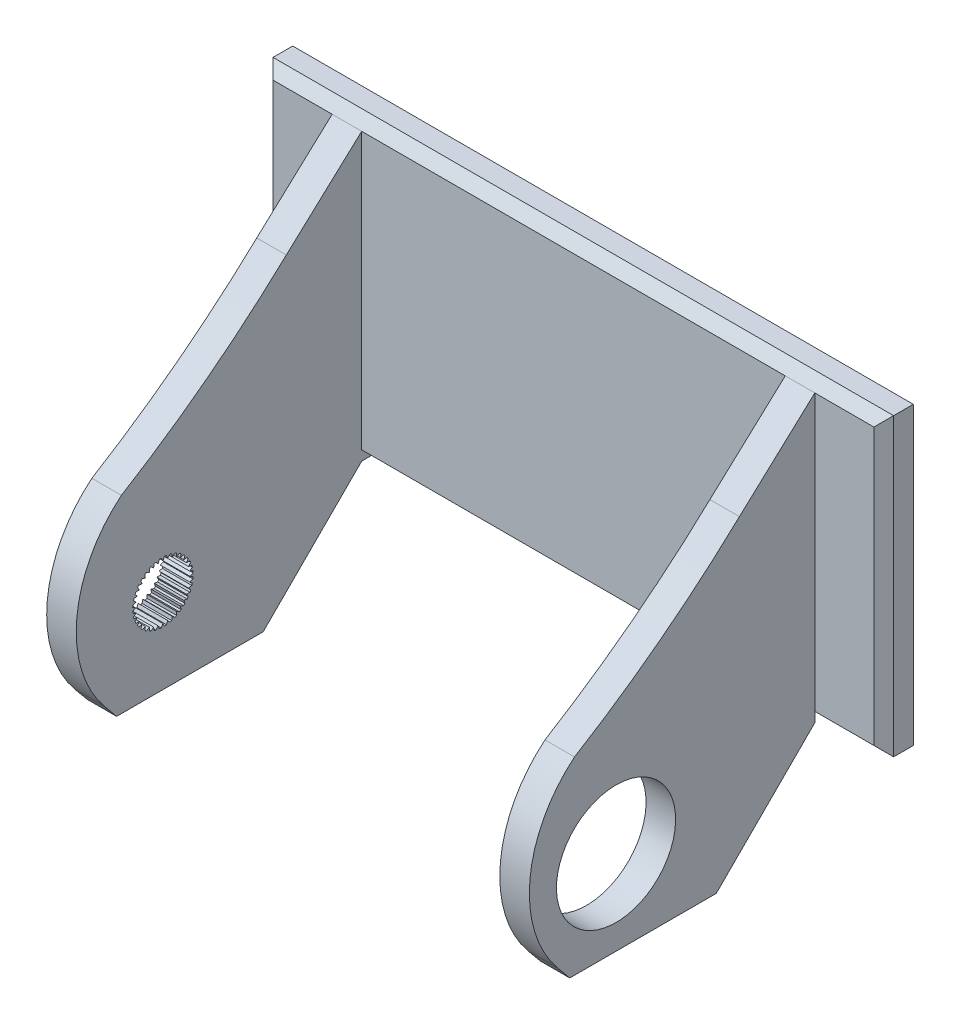
SolidWorks part; units mm, degrees
ref_plane "Front Plane" through (0, 0, 0) normal (0, 0, 1) x (1, 0, 0)
ref_plane "Top Plane" through (0, 0, 0) normal (0, 1, 0) x (1, 0, 0)
ref_plane "Right Plane" through (0, 0, 0) normal (1, 0, 0) x (0, 0, -1)
sketch "Sketch2" plane through (0, 0, 0) normal (0, 0, 1) x (1, 0, 0)
  line L1 (-31.5, -15) -> (31.5, -15)
  line L2 (-31.5, -15) -> (-31.5, 15)
  line L3 (-31.5, 15) -> (31.5, 15)
  line L4 (31.5, -15) -> (31.5, 15)
  point P4 (0, 15)
  point P6 (-31.5, 0)
  dimension "D1" = 63
  dimension "D2" = 30
extrude "Boss-Extrude2" add sketch "Sketch2" along normal blind 3
sketch "Sketch6" plane through (0, 0, 3) normal (0, 0, 1) x (1, 0, 0)
  line L0 (31.5, 15) -> (-31.5, 15) construction
  line L1 (-24.5, 15) -> (-21.5, 15)
  line L3 (-24.5, -15) -> (-21.5, -15)
  line L4 (-21.5, 15) -> (-21.5, -15)
  line L5 (-31.5, -15) -> (31.5, -15) construction
  line L7 (-24.5, 15) -> (-24.5, -15)
  dimension "D1" = 3
extrude "Boss-Extrude5" add sketch "Sketch6" along normal blind 20
sketch "Sketch7" plane through (0, -15, 0) normal (0, -1, 0) x (1, 0, 0)
  line L0 (-31.5, 0) -> (31.5, 0) construction
  line L1 (-24.5, 23) -> (-21.5, 23)
  line L2 (-24.5, 23) -> (-24.5, 0)
  line L3 (-24.5, 0) -> (-21.5, 0)
  line L4 (-21.5, 23) -> (-21.5, 0)
  point P7 (0, 0)
  dimension "D1" = 3
extrude "Boss-Extrude6" add sketch "Sketch7" along normal blind 10
sketch "Sketch8" plane through (0, 0, 23) normal (0, 0, 1) x (1, 0, 0)
  line L4 (-24.5, 15) -> (-24.5, -25)
  line L5 (-24.5, 15) -> (-24.5, -25)
  line L7 (-24.5, -25) -> (-21.5, -25)
  line L8 (-21.5, -25) -> (-21.5, 15)
  line L11 (-21.5, 15) -> (-24.5, 15)
  line L13 (-24.5, -25) -> (-21.5, -25)
  line L14 (-21.5, -25) -> (-21.5, 15)
  line L17 (-21.5, 15) -> (-24.5, 15)
  dimension "D1" = 0
extrude "Boss-Extrude7" add sketch "Sketch8" along normal blind 15
sketch "Sketch9" plane through (-24.5, 0, 0) normal (-1, 0, 0) x (0, 0, 1)
  line L288 (25.551, -14.882) -> (25.5973, -14.8018) construction
  line L289 (25.5298, -14.7054) -> (25.4386, -14.7215) construction
  line L290 (25.5973, -14.8018) -> (25.6299, -14.7454) construction
  line L291 (25.5939, -14.6941) -> (25.5298, -14.7054) construction
  line L292 (25.4711, -15.0204) -> (25.551, -14.882) construction
  line L293 (25.4386, -14.7215) -> (25.2812, -14.7493) construction
  line L294 (25.279, -14.4066) -> (25.3013, -14.3454) construction
  line L295 (25.257, -14.3011) -> (25.1958, -14.3233) construction
  line L296 (25.2473, -14.4936) -> (25.279, -14.4066) construction
  line L297 (25.1958, -14.3233) -> (25.1088, -14.355) construction
  line L298 (25.1927, -14.6438) -> (25.2473, -14.4936) construction
  line L299 (25.1088, -14.355) -> (24.9586, -14.4097) construction
  line L300 (24.8569, -13.9725) -> (24.8005, -14.0051) construction
  line L301 (24.8969, -14.0726) -> (24.9082, -14.0084) construction
  line L302 (24.8005, -14.0051) -> (24.7203, -14.0514) construction
  line L303 (24.8808, -14.1638) -> (24.8969, -14.0726) construction
  line L304 (24.7203, -14.0514) -> (24.5819, -14.1313) construction
  line L305 (24.8531, -14.3211) -> (24.8808, -14.1638) construction
  line L306 (25.6799, -15.4397) -> (25.7826, -15.3173) construction
  line L307 (25.6998, -15.1397) -> (25.54, -15.1397) construction
  line L308 (25.8421, -15.2464) -> (25.884, -15.1965) construction
  line L309 (25.8575, -15.1397) -> (25.7924, -15.1397) construction
  line L310 (25.7826, -15.3173) -> (25.8421, -15.2464) construction
  line L311 (25.7924, -15.1397) -> (25.6998, -15.1397) construction
  line L312 (26.006, -15.7267) -> (26.0559, -15.6848) construction
  line L313 (26.0397, -15.6243) -> (25.9756, -15.613) construction
  line L314 (25.9351, -15.7862) -> (26.006, -15.7267) construction
  line L315 (25.9756, -15.613) -> (25.8843, -15.5969) construction
  line L316 (25.8126, -15.8889) -> (25.9351, -15.7862) construction
  line L317 (25.8843, -15.5969) -> (25.727, -15.5692) construction
  line L318 (25.8654, -16.3543) -> (26.0038, -16.2744) construction
  line L319 (25.9867, -16.0792) -> (25.8366, -16.0246) construction
  line L320 (26.0038, -16.2744) -> (26.084, -16.2281) construction
  line L321 (26.0738, -16.1109) -> (25.9867, -16.0792) construction
  line L322 (26.084, -16.2281) -> (26.1404, -16.1956) construction
  line L323 (26.1349, -16.1332) -> (26.0738, -16.1109) construction
  line L324 (26.1404, -16.6509) -> (26.084, -16.6183) construction
  line L325 (26.0738, -16.7355) -> (26.1349, -16.7133) construction
  line L326 (26.084, -16.6183) -> (26.0038, -16.572) construction
  line L327 (25.9867, -16.7672) -> (26.0738, -16.7355) construction
  line L328 (26.0038, -16.572) -> (25.8654, -16.4921) construction
  line L329 (25.8366, -16.8219) -> (25.9867, -16.7672) construction
  line L330 (25.9756, -17.2334) -> (26.0397, -17.2221) construction
  line L331 (26.0559, -17.1616) -> (26.006, -17.1198) construction
  line L332 (25.8843, -17.2495) -> (25.9756, -17.2334) construction
  line L333 (26.006, -17.1198) -> (25.9351, -17.0602) construction
  line L334 (25.727, -17.2773) -> (25.8843, -17.2495) construction
  line L335 (25.9351, -17.0602) -> (25.8126, -16.9575) construction
  line L336 (25.6998, -17.7067) -> (25.7924, -17.7067) construction
  line L337 (25.8421, -17.6001) -> (25.7826, -17.5291) construction
  line L338 (25.54, -17.7067) -> (25.6998, -17.7067) construction
  line L339 (25.7826, -17.5291) -> (25.6799, -17.4067) construction
  line L340 (25.8654, -16.4921) -> (25.7461, -16.4232) construction
  line L341 (25.7461, -16.4232) -> (25.8654, -16.3543) construction
  line L342 (25.8366, -16.0246) -> (25.7071, -15.9775) construction
  line L343 (25.7071, -15.9775) -> (25.8126, -15.8889) construction
  line L344 (25.727, -15.5692) -> (25.5913, -15.5453) construction
  line L345 (25.5913, -15.5453) -> (25.6799, -15.4397) construction
  line L346 (25.54, -15.1397) -> (25.4022, -15.1397) construction
  line L347 (25.4022, -15.1397) -> (25.4711, -15.0204) construction
  line L348 (25.2812, -14.7493) -> (25.1456, -14.7732) construction
  line L349 (25.1456, -14.7732) -> (25.1927, -14.6438) construction
  line L350 (24.9586, -14.4097) -> (24.8292, -14.4568) construction
  line L351 (24.8292, -14.4568) -> (24.8531, -14.3211) construction
  line L352 (24.5819, -14.1313) -> (24.4626, -14.2001) construction
  line L353 (24.4626, -14.2001) -> (24.4626, -14.0624) construction
  line L354 (24.1626, -13.9225) -> (24.0571, -14.011) construction
  line L355 (24.0571, -14.011) -> (24.0332, -13.8754) construction
  line L356 (23.7134, -13.7897) -> (23.6249, -13.8952) construction
  line L357 (23.6249, -13.8952) -> (23.5778, -13.7658) construction
  line L358 (23.248, -13.7369) -> (23.1791, -13.8562) construction
  line L359 (23.1791, -13.8562) -> (23.1103, -13.7369) construction
  line L360 (22.7805, -13.7658) -> (22.7334, -13.8952) construction
  line L361 (22.7334, -13.8952) -> (22.6449, -13.7897) construction
  line L362 (22.3251, -13.8754) -> (22.3012, -14.011) construction
  line L363 (22.3012, -14.011) -> (22.1957, -13.9225) construction
  line L364 (21.8957, -14.0624) -> (21.8957, -14.2001) construction
  line L365 (21.8957, -14.2001) -> (21.7764, -14.1313) construction
  line L366 (21.5052, -14.3211) -> (21.5291, -14.4568) construction
  line L367 (21.5291, -14.4568) -> (21.3997, -14.4097) construction
  line L368 (21.1656, -14.6438) -> (21.2127, -14.7732) construction
  line L369 (21.2127, -14.7732) -> (21.0771, -14.7493) construction
  line L370 (20.8872, -15.0204) -> (20.9561, -15.1397) construction
  line L371 (20.9561, -15.1397) -> (20.8183, -15.1397) construction
  line L372 (20.6784, -15.4397) -> (20.767, -15.5453) construction
  line L373 (20.767, -15.5453) -> (20.6313, -15.5692) construction
  line L374 (20.5456, -15.8889) -> (20.6512, -15.9775) construction
  line L375 (20.6512, -15.9775) -> (20.5217, -16.0246) construction
  line L376 (20.4929, -16.3543) -> (20.6122, -16.4232) construction
  line L377 (20.6122, -16.4232) -> (20.4929, -16.4921) construction
  line L378 (20.5217, -16.8219) -> (20.6512, -16.869) construction
  line L379 (20.6512, -16.869) -> (20.5456, -16.9575) construction
  line L380 (20.6313, -17.2773) -> (20.767, -17.3012) construction
  line L381 (20.767, -17.3012) -> (20.6784, -17.4067) construction
  line L382 (20.8183, -17.7067) -> (20.9561, -17.7067) construction
  line L383 (20.9561, -17.7067) -> (20.8872, -17.826) construction
  line L384 (21.0771, -18.0972) -> (21.2127, -18.0732) construction
  line L385 (21.2127, -18.0732) -> (21.1656, -18.2027) construction
  line L386 (21.3997, -18.4368) -> (21.5291, -18.3896) construction
  line L387 (21.5291, -18.3896) -> (21.5052, -18.5253) construction
  line L388 (21.7764, -18.7152) -> (21.8957, -18.6463) construction
  line L389 (21.8957, -18.6463) -> (21.8957, -18.784) construction
  line L390 (22.1957, -18.9239) -> (22.3012, -18.8354) construction
  line L391 (22.3012, -18.8354) -> (22.3251, -18.971) construction
  line L392 (22.6449, -19.0567) -> (22.7334, -18.9512) construction
  line L393 (22.7334, -18.9512) -> (22.7805, -19.0806) construction
  line L394 (23.1103, -19.1095) -> (23.1791, -18.9902) construction
  line L395 (23.1791, -18.9902) -> (23.248, -19.1095) construction
  line L396 (23.5778, -19.0806) -> (23.6249, -18.9512) construction
  line L397 (23.6249, -18.9512) -> (23.7134, -19.0567) construction
  line L398 (24.0332, -18.971) -> (24.0571, -18.8354) construction
  line L399 (24.0571, -18.8354) -> (24.1626, -18.9239) construction
  line L400 (24.4626, -18.784) -> (24.4626, -18.6463) construction
  line L401 (24.4626, -18.6463) -> (24.5819, -18.7152) construction
  line L402 (24.8531, -18.5253) -> (24.8292, -18.3896) construction
  line L403 (24.8292, -18.3896) -> (24.9586, -18.4368) construction
  line L404 (25.1927, -18.2027) -> (25.1456, -18.0732) construction
  line L405 (25.1456, -18.0732) -> (25.2812, -18.0972) construction
  line L406 (25.4711, -17.826) -> (25.4022, -17.7067) construction
  line L407 (25.4022, -17.7067) -> (25.54, -17.7067) construction
  line L408 (25.6799, -17.4067) -> (25.5913, -17.3012) construction
  line L409 (25.5913, -17.3012) -> (25.727, -17.2773) construction
  line L410 (25.8126, -16.9575) -> (25.7071, -16.869) construction
  line L411 (25.7071, -16.869) -> (25.8366, -16.8219) construction
  line L412 (25.7924, -17.7067) -> (25.8575, -17.7067) construction
  line L413 (25.884, -17.6499) -> (25.8421, -17.6001) construction
  line L414 (25.6299, -18.101) -> (25.5973, -18.0446) construction
  line L415 (25.5298, -18.141) -> (25.5939, -18.1523) construction
  line L416 (25.5973, -18.0446) -> (25.551, -17.9644) construction
  line L417 (25.4386, -18.1249) -> (25.5298, -18.141) construction
  line L418 (24.9586, -18.4368) -> (25.1088, -18.4914) construction
  line L419 (25.2473, -18.3528) -> (25.1927, -18.2027) construction
  line L420 (25.1088, -18.4914) -> (25.1958, -18.5231) construction
  line L421 (25.279, -18.4399) -> (25.2473, -18.3528) construction
  line L422 (25.1958, -18.5231) -> (25.257, -18.5454) construction
  line L423 (25.3013, -18.5011) -> (25.279, -18.4399) construction
  line L424 (25.551, -17.9644) -> (25.4711, -17.826) construction
  line L425 (25.2812, -18.0972) -> (25.4386, -18.1249) construction
  line L426 (24.9082, -18.838) -> (24.8969, -18.7739) construction
  line L427 (24.8005, -18.8414) -> (24.8569, -18.8739) construction
  line L428 (24.8969, -18.7739) -> (24.8808, -18.6827) construction
  line L429 (24.7203, -18.7951) -> (24.8005, -18.8414) construction
  line L430 (24.8808, -18.6827) -> (24.8531, -18.5253) construction
  line L431 (24.5819, -18.7152) -> (24.7203, -18.7951) construction
  line L432 (22.8668, -19.3178) -> (22.8891, -19.379) construction
  line L433 (22.9515, -19.3845) -> (22.9841, -19.3281) construction
  line L434 (22.8352, -19.2308) -> (22.8668, -19.3178) construction
  line L435 (22.9841, -19.3281) -> (23.0304, -19.2479) construction
  line L436 (23.5231, -19.2308) -> (23.5778, -19.0806) construction
  line L437 (23.248, -19.1095) -> (23.3279, -19.2479) construction
  line L438 (23.4915, -19.3178) -> (23.5231, -19.2308) construction
  line L439 (23.3279, -19.2479) -> (23.3742, -19.3281) construction
  line L440 (23.4692, -19.379) -> (23.4915, -19.3178) construction
  line L441 (23.3742, -19.3281) -> (23.4068, -19.3845) construction
  line L442 (23.8757, -19.2501) -> (23.9175, -19.3) construction
  line L443 (23.978, -19.2838) -> (23.9894, -19.2196) construction
  line L444 (24.356, -19.0862) -> (24.4059, -19.128) construction
  line L445 (24.4626, -19.1016) -> (24.4626, -19.0365) construction
  line L446 (24.285, -19.0267) -> (24.356, -19.0862) construction
  line L447 (24.4626, -19.0365) -> (24.4626, -18.9438) construction
  line L448 (24.1626, -18.9239) -> (24.285, -19.0267) construction
  line L449 (24.4626, -18.9438) -> (24.4626, -18.784) construction
  line L450 (23.8162, -19.1791) -> (23.8757, -19.2501) construction
  line L451 (23.9894, -19.2196) -> (24.0054, -19.1284) construction
  line L452 (23.7134, -19.0567) -> (23.8162, -19.1791) construction
  line L453 (24.0054, -19.1284) -> (24.0332, -18.971) construction
  line L454 (22.7805, -19.0806) -> (22.8352, -19.2308) construction
  line L455 (23.0304, -19.2479) -> (23.1103, -19.1095) construction
  line L456 (22.3689, -19.2196) -> (22.3802, -19.2838) construction
  line L457 (22.4407, -19.3) -> (22.4826, -19.2501) construction
  line L458 (22.3529, -19.1284) -> (22.3689, -19.2196) construction
  line L459 (22.4826, -19.2501) -> (22.5421, -19.1791) construction
  line L460 (22.3251, -18.971) -> (22.3529, -19.1284) construction
  line L461 (22.5421, -19.1791) -> (22.6449, -19.0567) construction
  line L462 (21.8957, -19.0365) -> (21.8957, -19.1016) construction
  line L463 (21.9524, -19.128) -> (22.0023, -19.0862) construction
  line L464 (21.8957, -18.9438) -> (21.8957, -19.0365) construction
  line L465 (22.0023, -19.0862) -> (22.0733, -19.0267) construction
  line L466 (21.8957, -18.784) -> (21.8957, -18.9438) construction
  line L467 (22.0733, -19.0267) -> (22.1957, -18.9239) construction
  line L468 (21.4614, -18.7739) -> (21.4501, -18.838) construction
  line L469 (21.5014, -18.8739) -> (21.5578, -18.8414) construction
  line L470 (21.4775, -18.6827) -> (21.4614, -18.7739) construction
  line L471 (21.5578, -18.8414) -> (21.638, -18.7951) construction
  line L472 (21.5052, -18.5253) -> (21.4775, -18.6827) construction
  line L473 (21.638, -18.7951) -> (21.7764, -18.7152) construction
  line L474 (21.0793, -18.4399) -> (21.057, -18.5011) construction
  line L475 (21.1013, -18.5454) -> (21.1625, -18.5231) construction
  line L476 (21.111, -18.3528) -> (21.0793, -18.4399) construction
  line L477 (21.1625, -18.5231) -> (21.2495, -18.4914) construction
  line L478 (21.1656, -18.2027) -> (21.111, -18.3528) construction
  line L479 (21.2495, -18.4914) -> (21.3997, -18.4368) construction
  line L480 (20.7644, -18.1523) -> (20.8285, -18.141) construction
  line L481 (20.761, -18.0446) -> (20.7284, -18.101) construction
  line L482 (20.8285, -18.141) -> (20.9197, -18.1249) construction
  line L483 (20.8073, -17.9644) -> (20.761, -18.0446) construction
  line L484 (20.9197, -18.1249) -> (21.0771, -18.0972) construction
  line L485 (20.8872, -17.826) -> (20.8073, -17.9644) construction
  line L486 (20.5008, -17.7067) -> (20.5659, -17.7067) construction
  line L487 (20.5162, -17.6001) -> (20.4743, -17.6499) construction
  line L488 (20.5659, -17.7067) -> (20.6585, -17.7067) construction
  line L489 (20.5757, -17.5291) -> (20.5162, -17.6001) construction
  line L490 (20.6585, -17.7067) -> (20.8183, -17.7067) construction
  line L491 (20.6784, -17.4067) -> (20.5757, -17.5291) construction
  line L492 (20.3186, -17.2221) -> (20.3827, -17.2334) construction
  line L493 (20.3523, -17.1198) -> (20.3024, -17.1616) construction
  line L494 (20.3827, -17.2334) -> (20.4739, -17.2495) construction
  line L495 (20.4232, -17.0602) -> (20.3523, -17.1198) construction
  line L496 (20.4739, -17.2495) -> (20.6313, -17.2773) construction
  line L497 (20.5456, -16.9575) -> (20.4232, -17.0602) construction
  line L498 (20.2233, -16.7133) -> (20.2845, -16.7355) construction
  line L499 (20.2743, -16.6183) -> (20.2179, -16.6509) construction
  line L500 (20.3716, -16.7672) -> (20.5217, -16.8219) construction
  line L501 (20.4929, -16.4921) -> (20.3545, -16.572) construction
  line L502 (20.2845, -16.7355) -> (20.3716, -16.7672) construction
  line L503 (20.3545, -16.572) -> (20.2743, -16.6183) construction
  line L504 (20.2179, -16.1956) -> (20.2743, -16.2281) construction
  line L505 (20.2845, -16.1109) -> (20.2233, -16.1332) construction
  line L506 (20.2743, -16.2281) -> (20.3545, -16.2744) construction
  line L507 (20.3716, -16.0792) -> (20.2845, -16.1109) construction
  line L508 (20.3545, -16.2744) -> (20.4929, -16.3543) construction
  line L509 (20.5217, -16.0246) -> (20.3716, -16.0792) construction
  line L510 (20.3523, -15.7267) -> (20.4232, -15.7862) construction
  line L511 (20.4739, -15.5969) -> (20.3827, -15.613) construction
  line L512 (20.3024, -15.6848) -> (20.3523, -15.7267) construction
  line L513 (20.3827, -15.613) -> (20.3186, -15.6243) construction
  line L514 (20.4232, -15.7862) -> (20.5456, -15.8889) construction
  line L515 (20.6313, -15.5692) -> (20.4739, -15.5969) construction
  line L516 (20.5162, -15.2464) -> (20.5757, -15.3173) construction
  line L517 (20.6585, -15.1397) -> (20.5659, -15.1397) construction
  line L518 (20.4743, -15.1965) -> (20.5162, -15.2464) construction
  line L519 (20.5659, -15.1397) -> (20.5008, -15.1397) construction
  line L520 (20.5757, -15.3173) -> (20.6784, -15.4397) construction
  line L521 (20.8183, -15.1397) -> (20.6585, -15.1397) construction
  line L522 (20.7284, -14.7454) -> (20.761, -14.8018) construction
  line L523 (20.8285, -14.7054) -> (20.7644, -14.6941) construction
  line L524 (20.761, -14.8018) -> (20.8073, -14.882) construction
  line L525 (20.9197, -14.7215) -> (20.8285, -14.7054) construction
  line L526 (20.8073, -14.882) -> (20.8872, -15.0204) construction
  line L527 (21.0771, -14.7493) -> (20.9197, -14.7215) construction
  line L528 (21.1625, -14.3233) -> (21.1013, -14.3011) construction
  line L529 (21.057, -14.3454) -> (21.0793, -14.4066) construction
  line L530 (21.2495, -14.355) -> (21.1625, -14.3233) construction
  line L531 (21.0793, -14.4066) -> (21.111, -14.4936) construction
  line L532 (21.3997, -14.4097) -> (21.2495, -14.355) construction
  line L533 (21.111, -14.4936) -> (21.1656, -14.6438) construction
  line L534 (21.4501, -14.0084) -> (21.4614, -14.0726) construction
  line L535 (21.5578, -14.0051) -> (21.5014, -13.9725) construction
  line L536 (21.4614, -14.0726) -> (21.4775, -14.1638) construction
  line L537 (21.638, -14.0514) -> (21.5578, -14.0051) construction
  line L538 (21.4775, -14.1638) -> (21.5052, -14.3211) construction
  line L539 (21.7764, -14.1313) -> (21.638, -14.0514) construction
  line L540 (21.8957, -13.7449) -> (21.8957, -13.81) construction
  line L541 (22.0023, -13.7602) -> (21.9524, -13.7184) construction
  line L542 (21.8957, -13.81) -> (21.8957, -13.9026) construction
  line L543 (22.0733, -13.8198) -> (22.0023, -13.7602) construction
  line L544 (21.8957, -13.9026) -> (21.8957, -14.0624) construction
  line L545 (22.1957, -13.9225) -> (22.0733, -13.8198) construction
  line L546 (22.3802, -13.5627) -> (22.3689, -13.6268) construction
  line L547 (22.4826, -13.5963) -> (22.4407, -13.5465) construction
  line L548 (22.3689, -13.6268) -> (22.3529, -13.718) construction
  line L549 (22.5421, -13.6673) -> (22.4826, -13.5963) construction
  line L550 (22.3529, -13.718) -> (22.3251, -13.8754) construction
  line L551 (22.6449, -13.7897) -> (22.5421, -13.6673) construction
  line L552 (24.356, -13.7602) -> (24.285, -13.8198) construction
  line L553 (24.4626, -13.9026) -> (24.4626, -13.81) construction
  line L554 (24.4059, -13.7184) -> (24.356, -13.7602) construction
  line L555 (24.4626, -13.81) -> (24.4626, -13.7449) construction
  line L556 (24.285, -13.8198) -> (24.1626, -13.9225) construction
  line L557 (24.4626, -14.0624) -> (24.4626, -13.9026) construction
  line L558 (23.9894, -13.6268) -> (23.978, -13.5627) construction
  line L559 (23.9175, -13.5465) -> (23.8757, -13.5963) construction
  line L560 (24.0054, -13.718) -> (23.9894, -13.6268) construction
  line L561 (23.8757, -13.5963) -> (23.8162, -13.6673) construction
  line L562 (24.0332, -13.8754) -> (24.0054, -13.718) construction
  line L563 (23.8162, -13.6673) -> (23.7134, -13.7897) construction
  line L564 (23.4915, -13.5286) -> (23.4692, -13.4674) construction
  line L565 (23.4068, -13.462) -> (23.3742, -13.5183) construction
  line L566 (23.5231, -13.6156) -> (23.4915, -13.5286) construction
  line L567 (23.3742, -13.5183) -> (23.3279, -13.5986) construction
  line L568 (23.5778, -13.7658) -> (23.5231, -13.6156) construction
  line L569 (23.3279, -13.5986) -> (23.248, -13.7369) construction
  line L570 (22.8891, -13.4674) -> (22.8668, -13.5286) construction
  line L571 (22.9841, -13.5183) -> (22.9515, -13.462) construction
  line L572 (22.8668, -13.5286) -> (22.8352, -13.6156) construction
  line L573 (23.0304, -13.5986) -> (22.9841, -13.5183) construction
  line L574 (22.8352, -13.6156) -> (22.7805, -13.7658) construction
  line L575 (23.1103, -13.7369) -> (23.0304, -13.5986) construction
  line L576 (25.6376, -14.932) -> (25.6839, -14.8518)
  line L577 (25.6839, -14.8518) -> (25.7476, -14.7415)
  line L578 (25.6379, -14.5848) -> (25.5124, -14.607)
  line L579 (25.5124, -14.607) -> (25.4212, -14.623)
  line L580 (25.4212, -14.623) -> (25.2988, -14.6446)
  line L581 (25.2988, -14.6446) -> (25.3413, -14.5278)
  line L582 (25.3413, -14.5278) -> (25.373, -14.4408)
  line L583 (25.373, -14.4408) -> (25.4165, -14.3211)
  line L584 (25.2813, -14.1858) -> (25.1616, -14.2294)
  line L585 (25.1616, -14.2294) -> (25.0746, -14.2611)
  line L586 (25.0746, -14.2611) -> (24.9577, -14.3036)
  line L587 (24.9577, -14.3036) -> (24.9793, -14.1811)
  line L588 (24.9793, -14.1811) -> (24.9954, -14.0899)
  line L589 (24.9954, -14.0899) -> (25.0175, -13.9645)
  line L590 (24.8608, -13.8548) -> (24.7505, -13.9185)
  line L591 (24.7505, -13.9185) -> (24.6703, -13.9648)
  line L592 (24.6703, -13.9648) -> (24.5626, -14.0269)
  line L593 (24.5626, -14.0269) -> (24.5626, -13.9026)
  line L594 (24.5626, -13.9026) -> (24.5626, -13.81)
  line L595 (24.5626, -13.81) -> (24.5626, -13.6826)
  line L596 (24.3893, -13.6018) -> (24.2917, -13.6836)
  line L597 (24.2917, -13.6836) -> (24.2208, -13.7432)
  line L598 (24.2208, -13.7432) -> (24.1255, -13.8231)
  line L599 (24.1255, -13.8231) -> (24.1039, -13.7007)
  line L600 (24.1039, -13.7007) -> (24.0878, -13.6094)
  line L601 (24.0878, -13.6094) -> (24.0657, -13.484)
  line L602 (23.8809, -13.4345) -> (23.7991, -13.5321)
  line L603 (23.7991, -13.5321) -> (23.7395, -13.603)
  line L604 (23.7395, -13.603) -> (23.6596, -13.6983)
  line L605 (23.6596, -13.6983) -> (23.6171, -13.5814)
  line L606 (23.6171, -13.5814) -> (23.5854, -13.4944)
  line L607 (23.5854, -13.4944) -> (23.5419, -13.3747)
  line L608 (23.3513, -13.358) -> (23.2876, -13.4683)
  line L609 (23.2876, -13.4683) -> (23.2413, -13.5486)
  line L610 (23.2413, -13.5486) -> (23.1791, -13.6562)
  line L611 (23.1791, -13.6562) -> (23.117, -13.5486)
  line L612 (23.117, -13.5486) -> (23.0707, -13.4683)
  line L613 (23.0707, -13.4683) -> (23.007, -13.358)
  line L614 (22.8164, -13.3747) -> (22.7729, -13.4944)
  line L615 (22.7729, -13.4944) -> (22.7412, -13.5814)
  line L616 (22.7412, -13.5814) -> (22.6987, -13.6983)
  line L617 (22.6987, -13.6983) -> (22.6187, -13.603)
  line L618 (22.6187, -13.603) -> (22.5592, -13.5321)
  line L619 (22.5592, -13.5321) -> (22.4773, -13.4345)
  line L620 (22.2926, -13.484) -> (22.2705, -13.6094)
  line L621 (22.2705, -13.6094) -> (22.2544, -13.7007)
  line L622 (22.2544, -13.7007) -> (22.2328, -13.8231)
  line L623 (22.2328, -13.8231) -> (22.1375, -13.7432)
  line L624 (22.1375, -13.7432) -> (22.0666, -13.6836)
  line L625 (22.0666, -13.6836) -> (21.969, -13.6018)
  line L626 (21.7957, -13.6826) -> (21.7957, -13.81)
  line L627 (21.7957, -13.81) -> (21.7957, -13.9026)
  line L628 (21.7957, -13.9026) -> (21.7957, -14.0269)
  line L629 (21.7957, -14.0269) -> (21.688, -13.9648)
  line L630 (21.688, -13.9648) -> (21.6078, -13.9185)
  line L631 (21.6078, -13.9185) -> (21.4975, -13.8548)
  line L632 (21.3408, -13.9645) -> (21.3629, -14.0899)
  line L633 (21.3629, -14.0899) -> (21.379, -14.1811)
  line L634 (21.379, -14.1811) -> (21.4006, -14.3036)
  line L635 (21.4006, -14.3036) -> (21.2837, -14.2611)
  line L636 (21.2837, -14.2611) -> (21.1967, -14.2294)
  line L637 (21.1967, -14.2294) -> (21.077, -14.1858)
  line L638 (20.9417, -14.3211) -> (20.9853, -14.4408)
  line L639 (20.9853, -14.4408) -> (21.017, -14.5278)
  line L640 (21.017, -14.5278) -> (21.0595, -14.6446)
  line L641 (21.0595, -14.6446) -> (20.9371, -14.623)
  line L642 (20.9371, -14.623) -> (20.8458, -14.607)
  line L643 (20.8458, -14.607) -> (20.7204, -14.5848)
  line L644 (20.6107, -14.7415) -> (20.6744, -14.8518)
  line L645 (20.6744, -14.8518) -> (20.7207, -14.932)
  line L646 (20.7207, -14.932) -> (20.7829, -15.0397)
  line L647 (20.7829, -15.0397) -> (20.6585, -15.0397)
  line L648 (20.6585, -15.0397) -> (20.5659, -15.0397)
  line L649 (20.5659, -15.0397) -> (20.4386, -15.0397)
  line L650 (20.3577, -15.2131) -> (20.4396, -15.3107)
  line L651 (20.4396, -15.3107) -> (20.4991, -15.3816)
  line L652 (20.4991, -15.3816) -> (20.579, -15.4769)
  line L653 (20.579, -15.4769) -> (20.4566, -15.4984)
  line L654 (20.4566, -15.4984) -> (20.3654, -15.5145)
  line L655 (20.3654, -15.5145) -> (20.2399, -15.5366)
  line L656 (20.1904, -15.7214) -> (20.288, -15.8033)
  line L657 (20.288, -15.8033) -> (20.3589, -15.8628)
  line L658 (20.3589, -15.8628) -> (20.4542, -15.9427)
  line L659 (20.4542, -15.9427) -> (20.3374, -15.9853)
  line L660 (20.3374, -15.9853) -> (20.2503, -16.0169)
  line L661 (20.2503, -16.0169) -> (20.1306, -16.0605)
  line L662 (20.114, -16.2511) -> (20.2243, -16.3147)
  line L663 (20.2243, -16.3147) -> (20.3045, -16.3611)
  line L664 (20.3045, -16.3611) -> (20.4122, -16.4232)
  line L665 (20.4122, -16.4232) -> (20.3045, -16.4854)
  line L666 (20.3045, -16.4854) -> (20.2243, -16.5317)
  line L667 (20.2243, -16.5317) -> (20.114, -16.5954)
  line L668 (20.1306, -16.7859) -> (20.2503, -16.8295)
  line L669 (20.2503, -16.8295) -> (20.3374, -16.8612)
  line L670 (20.3374, -16.8612) -> (20.4542, -16.9037)
  line L671 (20.4542, -16.9037) -> (20.3589, -16.9836)
  line L672 (20.3589, -16.9836) -> (20.288, -17.0432)
  line L673 (20.288, -17.0432) -> (20.1904, -17.125)
  line L674 (20.2399, -17.3098) -> (20.3654, -17.3319)
  line L675 (20.3654, -17.3319) -> (20.4566, -17.348)
  line L676 (20.4566, -17.348) -> (20.579, -17.3696)
  line L677 (20.579, -17.3696) -> (20.4991, -17.4648)
  line L678 (20.4991, -17.4648) -> (20.4396, -17.5358)
  line L679 (20.4396, -17.5358) -> (20.3577, -17.6333)
  line L680 (20.4386, -17.8067) -> (20.5659, -17.8067)
  line L681 (20.5659, -17.8067) -> (20.6585, -17.8067)
  line L682 (20.6585, -17.8067) -> (20.7829, -17.8067)
  line L683 (20.7829, -17.8067) -> (20.7207, -17.9144)
  line L684 (20.7207, -17.9144) -> (20.6744, -17.9946)
  line L685 (20.6744, -17.9946) -> (20.6107, -18.1049)
  line L686 (20.7204, -18.2616) -> (20.8458, -18.2395)
  line L687 (20.8458, -18.2395) -> (20.9371, -18.2234)
  line L688 (20.9371, -18.2234) -> (21.0595, -18.2018)
  line L689 (21.0595, -18.2018) -> (21.017, -18.3186)
  line L690 (21.017, -18.3186) -> (20.9853, -18.4057)
  line L691 (20.9853, -18.4057) -> (20.9417, -18.5253)
  line L692 (21.077, -18.6606) -> (21.1967, -18.6171)
  line L693 (21.1967, -18.6171) -> (21.2837, -18.5854)
  line L694 (21.2837, -18.5854) -> (21.4006, -18.5429)
  line L695 (21.4006, -18.5429) -> (21.379, -18.6653)
  line L696 (21.379, -18.6653) -> (21.3629, -18.7565)
  line L697 (21.3629, -18.7565) -> (21.3408, -18.8819)
  line L698 (21.4975, -18.9917) -> (21.6078, -18.928)
  line L699 (21.6078, -18.928) -> (21.688, -18.8817)
  line L700 (21.688, -18.8817) -> (21.7957, -18.8195)
  line L701 (21.7957, -18.8195) -> (21.7957, -18.9438)
  line L702 (21.7957, -18.9438) -> (21.7957, -19.0365)
  line L703 (21.7957, -19.0365) -> (21.7957, -19.1638)
  line L704 (21.969, -19.2447) -> (22.0666, -19.1628)
  line L705 (22.0666, -19.1628) -> (22.1375, -19.1033)
  line L706 (22.1375, -19.1033) -> (22.2328, -19.0233)
  line L707 (22.2328, -19.0233) -> (22.2544, -19.1458)
  line L708 (22.2544, -19.1458) -> (22.2705, -19.237)
  line L709 (22.2705, -19.237) -> (22.2926, -19.3624)
  line L710 (22.4773, -19.4119) -> (22.5592, -19.3144)
  line L711 (22.5592, -19.3144) -> (22.6187, -19.2434)
  line L712 (22.6187, -19.2434) -> (22.6987, -19.1482)
  line L713 (22.6987, -19.1482) -> (22.7412, -19.265)
  line L714 (22.7412, -19.265) -> (22.7729, -19.352)
  line L715 (22.7729, -19.352) -> (22.8164, -19.4717)
  line L716 (23.007, -19.4884) -> (23.0707, -19.3781)
  line L717 (23.0707, -19.3781) -> (23.117, -19.2979)
  line L718 (23.117, -19.2979) -> (23.1791, -19.1902)
  line L719 (23.1791, -19.1902) -> (23.2413, -19.2979)
  line L720 (23.2413, -19.2979) -> (23.2876, -19.3781)
  line L721 (23.2876, -19.3781) -> (23.3513, -19.4884)
  line L722 (23.5419, -19.4717) -> (23.5854, -19.352)
  line L723 (23.5854, -19.352) -> (23.6171, -19.265)
  line L724 (23.6171, -19.265) -> (23.6596, -19.1482)
  line L725 (23.6596, -19.1482) -> (23.7395, -19.2434)
  line L726 (23.7395, -19.2434) -> (23.7991, -19.3144)
  line L727 (23.7991, -19.3144) -> (23.8809, -19.4119)
  line L728 (24.0657, -19.3624) -> (24.0878, -19.237)
  line L729 (24.0878, -19.237) -> (24.1039, -19.1458)
  line L730 (24.1039, -19.1458) -> (24.1255, -19.0233)
  line L731 (24.1255, -19.0233) -> (24.2208, -19.1033)
  line L732 (24.2208, -19.1033) -> (24.2917, -19.1628)
  line L733 (24.2917, -19.1628) -> (24.3893, -19.2447)
  line L734 (24.5626, -19.1638) -> (24.5626, -19.0365)
  line L735 (24.5626, -19.0365) -> (24.5626, -18.9438)
  line L736 (24.5626, -18.9438) -> (24.5626, -18.8195)
  line L737 (24.5626, -18.8195) -> (24.6703, -18.8817)
  line L738 (24.6703, -18.8817) -> (24.7505, -18.928)
  line L739 (24.7505, -18.928) -> (24.8608, -18.9917)
  line L740 (25.0175, -18.8819) -> (24.9954, -18.7565)
  line L741 (24.9954, -18.7565) -> (24.9793, -18.6653)
  line L742 (24.9793, -18.6653) -> (24.9577, -18.5429)
  line L743 (24.9577, -18.5429) -> (25.0746, -18.5854)
  line L744 (25.0746, -18.5854) -> (25.1616, -18.6171)
  line L745 (25.1616, -18.6171) -> (25.2813, -18.6606)
  line L746 (25.4165, -18.5253) -> (25.373, -18.4057)
  line L747 (25.373, -18.4057) -> (25.3413, -18.3186)
  line L748 (25.3413, -18.3186) -> (25.2988, -18.2018)
  line L749 (25.2988, -18.2018) -> (25.4212, -18.2234)
  line L750 (25.4212, -18.2234) -> (25.5124, -18.2395)
  line L751 (25.5124, -18.2395) -> (25.6379, -18.2616)
  line L752 (25.7476, -18.1049) -> (25.6839, -17.9946)
  line L753 (25.6839, -17.9946) -> (25.6376, -17.9144)
  line L754 (25.6376, -17.9144) -> (25.5754, -17.8067)
  line L755 (25.5754, -17.8067) -> (25.6998, -17.8067)
  line L756 (25.6998, -17.8067) -> (25.7924, -17.8067)
  line L757 (25.7924, -17.8067) -> (25.9197, -17.8067)
  line L758 (26.0006, -17.6333) -> (25.9187, -17.5358)
  line L759 (25.9187, -17.5358) -> (25.8592, -17.4648)
  line L760 (25.8592, -17.4648) -> (25.7793, -17.3696)
  line L761 (25.7793, -17.3696) -> (25.9017, -17.348)
  line L762 (25.9017, -17.348) -> (25.9929, -17.3319)
  line L763 (25.9929, -17.3319) -> (26.1183, -17.3098)
  line L764 (26.1679, -17.125) -> (26.0703, -17.0432)
  line L765 (26.0703, -17.0432) -> (25.9993, -16.9836)
  line L766 (25.9993, -16.9836) -> (25.9041, -16.9037)
  line L767 (25.9041, -16.9037) -> (26.0209, -16.8612)
  line L768 (26.0209, -16.8612) -> (26.108, -16.8295)
  line L769 (26.108, -16.8295) -> (26.2276, -16.7859)
  line L770 (26.2443, -16.5954) -> (26.134, -16.5317)
  line L771 (26.134, -16.5317) -> (26.0538, -16.4854)
  line L772 (26.0538, -16.4854) -> (25.9461, -16.4232)
  line L773 (25.9461, -16.4232) -> (26.0538, -16.3611)
  line L774 (26.0538, -16.3611) -> (26.134, -16.3147)
  line L775 (26.134, -16.3147) -> (26.2443, -16.2511)
  line L776 (26.2276, -16.0605) -> (26.108, -16.0169)
  line L777 (26.108, -16.0169) -> (26.0209, -15.9853)
  line L778 (26.0209, -15.9853) -> (25.9041, -15.9427)
  line L779 (25.9041, -15.9427) -> (25.9993, -15.8628)
  line L780 (25.9993, -15.8628) -> (26.0703, -15.8033)
  line L781 (26.0703, -15.8033) -> (26.1679, -15.7214)
  line L782 (26.1183, -15.5366) -> (25.9929, -15.5145)
  line L783 (25.9929, -15.5145) -> (25.9017, -15.4984)
  line L784 (25.9017, -15.4984) -> (25.7793, -15.4769)
  line L785 (25.7793, -15.4769) -> (25.8592, -15.3816)
  line L786 (25.8592, -15.3816) -> (25.9187, -15.3107)
  line L787 (25.9187, -15.3107) -> (26.0006, -15.2131)
  line L788 (25.9197, -15.0397) -> (25.7924, -15.0397)
  line L789 (25.7924, -15.0397) -> (25.6998, -15.0397)
  line L790 (25.6998, -15.0397) -> (25.5754, -15.0397)
  line L791 (25.5754, -15.0397) -> (25.6376, -14.932)
  arc A37 (25.6299, -14.7454) -> (25.5939, -14.6941) centre (23.1791, -16.4232) ccw construction
  arc A38 (25.3013, -14.3454) -> (25.257, -14.3011) centre (23.1791, -16.4232) ccw construction
  arc A39 (24.9082, -14.0084) -> (24.8569, -13.9725) centre (23.1791, -16.4232) ccw construction
  arc A40 (25.884, -15.1965) -> (25.8575, -15.1397) centre (23.1791, -16.4232) ccw construction
  arc A41 (26.0559, -15.6848) -> (26.0397, -15.6243) centre (23.1791, -16.4232) ccw construction
  arc A42 (26.1404, -16.1956) -> (26.1349, -16.1332) centre (23.1791, -16.4232) ccw construction
  arc A43 (26.1349, -16.7133) -> (26.1404, -16.6509) centre (23.1791, -16.4232) ccw construction
  arc A44 (26.0397, -17.2221) -> (26.0559, -17.1616) centre (23.1791, -16.4232) ccw construction
  arc A45 (25.8575, -17.7067) -> (25.884, -17.6499) centre (23.1791, -16.4232) ccw construction
  arc A46 (25.5939, -18.1523) -> (25.6299, -18.101) centre (23.1791, -16.4232) ccw construction
  arc A47 (25.257, -18.5454) -> (25.3013, -18.5011) centre (23.1791, -16.4232) ccw construction
  arc A48 (24.8569, -18.8739) -> (24.9082, -18.838) centre (23.1791, -16.4232) ccw construction
  arc A49 (22.8891, -19.379) -> (22.9515, -19.3845) centre (23.1791, -16.4232) ccw construction
  arc A50 (23.4068, -19.3845) -> (23.4692, -19.379) centre (23.1791, -16.4232) ccw construction
  arc A51 (23.9175, -19.3) -> (23.978, -19.2838) centre (23.1791, -16.4232) ccw construction
  arc A52 (24.4059, -19.128) -> (24.4626, -19.1016) centre (23.1791, -16.4232) ccw construction
  arc A53 (22.3802, -19.2838) -> (22.4407, -19.3) centre (23.1791, -16.4232) ccw construction
  arc A54 (21.8957, -19.1016) -> (21.9524, -19.128) centre (23.1791, -16.4232) ccw construction
  arc A55 (21.4501, -18.838) -> (21.5014, -18.8739) centre (23.1791, -16.4232) ccw construction
  arc A56 (21.057, -18.5011) -> (21.1013, -18.5454) centre (23.1791, -16.4232) ccw construction
  arc A57 (20.7284, -18.101) -> (20.7644, -18.1523) centre (23.1791, -16.4232) ccw construction
  arc A58 (20.4743, -17.6499) -> (20.5008, -17.7067) centre (23.1791, -16.4232) ccw construction
  arc A59 (20.3024, -17.1616) -> (20.3186, -17.2221) centre (23.1791, -16.4232) ccw construction
  arc A60 (20.2179, -16.6509) -> (20.2233, -16.7133) centre (23.1791, -16.4232) ccw construction
  arc A61 (20.2233, -16.1332) -> (20.2179, -16.1956) centre (23.1791, -16.4232) ccw construction
  arc A62 (20.3186, -15.6243) -> (20.3024, -15.6848) centre (23.1791, -16.4232) ccw construction
  arc A63 (20.5008, -15.1397) -> (20.4743, -15.1965) centre (23.1791, -16.4232) ccw construction
  arc A64 (20.7644, -14.6941) -> (20.7284, -14.7454) centre (23.1791, -16.4232) ccw construction
  arc A65 (21.1013, -14.3011) -> (21.057, -14.3454) centre (23.1791, -16.4232) ccw construction
  arc A66 (21.5014, -13.9725) -> (21.4501, -14.0084) centre (23.1791, -16.4232) ccw construction
  arc A67 (21.9524, -13.7184) -> (21.8957, -13.7449) centre (23.1791, -16.4232) ccw construction
  arc A68 (22.4407, -13.5465) -> (22.3802, -13.5627) centre (23.1791, -16.4232) ccw construction
  arc A69 (24.4626, -13.7449) -> (24.4059, -13.7184) centre (23.1791, -16.4232) ccw construction
  arc A70 (23.978, -13.5627) -> (23.9175, -13.5465) centre (23.1791, -16.4232) ccw construction
  arc A71 (23.4692, -13.4674) -> (23.4068, -13.462) centre (23.1791, -16.4232) ccw construction
  arc A72 (22.9515, -13.462) -> (22.8891, -13.4674) centre (23.1791, -16.4232) ccw construction
  arc A73 (25.7476, -14.7415) -> (25.6379, -14.5848) centre (23.1791, -16.4232) ccw
  arc A74 (25.4165, -14.3211) -> (25.2813, -14.1858) centre (23.1791, -16.4232) ccw
  arc A75 (25.0175, -13.9645) -> (24.8608, -13.8548) centre (23.1791, -16.4232) ccw
  arc A76 (24.5626, -13.6826) -> (24.3893, -13.6018) centre (23.1791, -16.4232) ccw
  arc A77 (24.0657, -13.484) -> (23.8809, -13.4345) centre (23.1791, -16.4232) ccw
  arc A78 (23.5419, -13.3747) -> (23.3513, -13.358) centre (23.1791, -16.4232) ccw
  arc A79 (23.007, -13.358) -> (22.8164, -13.3747) centre (23.1791, -16.4232) ccw
  arc A80 (22.4773, -13.4345) -> (22.2926, -13.484) centre (23.1791, -16.4232) ccw
  arc A81 (21.969, -13.6018) -> (21.7957, -13.6826) centre (23.1791, -16.4232) ccw
  arc A82 (21.4975, -13.8548) -> (21.3408, -13.9645) centre (23.1791, -16.4232) ccw
  arc A83 (21.077, -14.1858) -> (20.9417, -14.3211) centre (23.1791, -16.4232) ccw
  arc A84 (20.7204, -14.5848) -> (20.6107, -14.7415) centre (23.1791, -16.4232) ccw
  arc A85 (20.4386, -15.0397) -> (20.3577, -15.2131) centre (23.1791, -16.4232) ccw
  arc A86 (20.2399, -15.5366) -> (20.1904, -15.7214) centre (23.1791, -16.4232) ccw
  arc A87 (20.1306, -16.0605) -> (20.114, -16.2511) centre (23.1791, -16.4232) ccw
  arc A88 (20.114, -16.5954) -> (20.1306, -16.7859) centre (23.1791, -16.4232) ccw
  arc A89 (20.1904, -17.125) -> (20.2399, -17.3098) centre (23.1791, -16.4232) ccw
  arc A90 (20.3577, -17.6333) -> (20.4386, -17.8067) centre (23.1791, -16.4232) ccw
  arc A91 (20.6107, -18.1049) -> (20.7204, -18.2616) centre (23.1791, -16.4232) ccw
  arc A92 (20.9417, -18.5253) -> (21.077, -18.6606) centre (23.1791, -16.4232) ccw
  arc A93 (21.3408, -18.8819) -> (21.4975, -18.9917) centre (23.1791, -16.4232) ccw
  arc A94 (21.7957, -19.1638) -> (21.969, -19.2447) centre (23.1791, -16.4232) ccw
  arc A95 (22.2926, -19.3624) -> (22.4773, -19.4119) centre (23.1791, -16.4232) ccw
  arc A96 (22.8164, -19.4717) -> (23.007, -19.4884) centre (23.1791, -16.4232) ccw
  arc A97 (23.3513, -19.4884) -> (23.5419, -19.4717) centre (23.1791, -16.4232) ccw
  arc A98 (23.8809, -19.4119) -> (24.0657, -19.3624) centre (23.1791, -16.4232) ccw
  arc A99 (24.3893, -19.2447) -> (24.5626, -19.1638) centre (23.1791, -16.4232) ccw
  arc A100 (24.8608, -18.9917) -> (25.0175, -18.8819) centre (23.1791, -16.4232) ccw
  arc A101 (25.2813, -18.6606) -> (25.4165, -18.5253) centre (23.1791, -16.4232) ccw
  arc A102 (25.6379, -18.2616) -> (25.7476, -18.1049) centre (23.1791, -16.4232) ccw
  arc A103 (25.9197, -17.8067) -> (26.0006, -17.6333) centre (23.1791, -16.4232) ccw
  arc A104 (26.1183, -17.3098) -> (26.1679, -17.125) centre (23.1791, -16.4232) ccw
  arc A105 (26.2276, -16.7859) -> (26.2443, -16.5954) centre (23.1791, -16.4232) ccw
  arc A106 (26.2443, -16.2511) -> (26.2276, -16.0605) centre (23.1791, -16.4232) ccw
  arc A107 (26.1679, -15.7214) -> (26.1183, -15.5366) centre (23.1791, -16.4232) ccw
  arc A108 (26.0006, -15.2131) -> (25.9197, -15.0397) centre (23.1791, -16.4232) ccw
extrude "Cut-Extrude2" cut sketch "Sketch9" against normal blind 15
sketch "Sketch10" plane through (-24.5, 0, 0) normal (-1, 0, 0) x (0, 0, 1)
  line L0 (29.1218, -23.4869) -> (27.8782, -25)
  line L1 (38, -25) -> (0, -25) construction
  line L2 (3, -15) -> (13, -25)
  line L3 (13, -25) -> (27.8782, -25)
  line L4 (0, -25) -> (38, -25)
  line L5 (38, -25) -> (38, 15)
  line L6 (38, 15) -> (3, 15)
  line L7 (0, -25) -> (0, -15)
  line L8 (0, -15) -> (3, -15)
  arc A0 (3, 15) -> (27.393, -5.8086) centre (79.911, 80.4574) ccw
  arc A1 (27.393, -5.8086) -> (29.1218, -23.4869) centre (19.4183, -15.5121) cw
  dimension "D1" = 45
extrude "Cut-Extrude3" cut sketch "Sketch10" against normal blind 15 contours A0 A1 L0 L4 L5 L6 | L8 L7 L4 L2
chamfer "Chamfer2" distance 1 angle 45 6 edges at (5, -15, 3) (31.5, 0, 3) (5, 15, 3) (-28, -15, 3) (-28, 15, 3) (-31.5, 0, 3)
sketch "Sketch11" plane through (-24.5, 0, 0) normal (-1, 0, 0) x (0, 0, 1)
  line L0 (2, 15) -> (3, 14)
  line L1 (3, 14) -> (12.3239, 5.411)
  line L2 (12.3239, 5.411) -> (3, 15)
  line L3 (3, 15) -> (2, 15)
extrude "Cut-Extrude4" cut sketch "Sketch11" against normal blind 15
mirror "Mirror1" about plane through (0, 0, 0) normal (1, 0, 0) of "Boss-Extrude7", "Boss-Extrude6", "Boss-Extrude5"
mirror "Mirror2" about plane through (0, 0, 0) normal (1, 0, 0) of "Cut-Extrude4", "Cut-Extrude2", "Cut-Extrude3"
sketch "Sketch12" plane through (24.5, 0, 0) normal (1, 0, 0) x (0, 0, -1)
  circle A0 centre (-23.1791, -16.4232) radius 6.05
  dimension "D1" = 12.1
extrude "Cut-Extrude5" cut sketch "Sketch12" against normal blind 10
